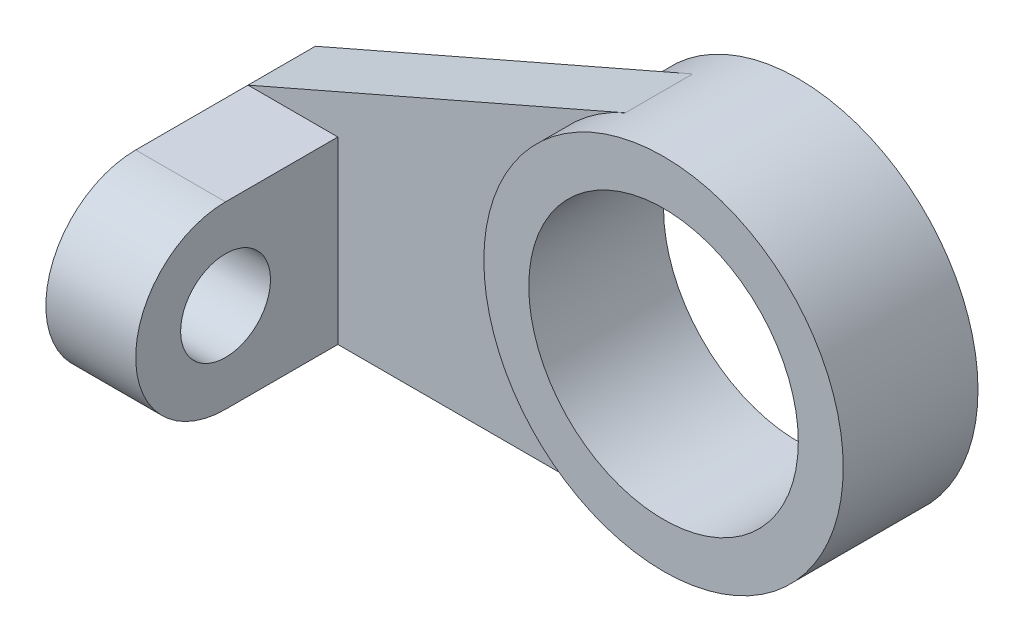
SolidWorks part; units mm, degrees
ref_plane "Front Plane" through (0, 0, 0) normal (0, 0, 1) x (1, 0, 0)
ref_plane "Top Plane" through (0, 0, 0) normal (0, 1, 0) x (1, 0, 0)
ref_plane "Right Plane" through (0, 0, 0) normal (1, 0, 0) x (0, 0, -1)
sketch "Sketch1" plane through (0, 0, 0) normal (0, 0, 1) x (1, 0, 0)
  circle A0 centre (0, 0) radius 38.1
  circle A1 centre (0, 0) radius 50.8
  dimension "D1" = 76.2
  dimension "D2" = 101.6
extrude "Boss-Extrude1" add sketch "Sketch1" along normal mid plane 38.1 contours A0 | A1
sketch "Sketch2" plane through (0, 0, 0) normal (0, 0, 1) x (1, 0, 0)
  line L0 (0, -50.8) -> (-127, -50.8)
  line L1 (-127, -50.8) -> (-127, 0)
  line L2 (-127, 0) -> (-20.32, 46.559)
  circle A0 centre (0, 0) radius 50.8 construction
  arc A1 (-20.32, 46.559) -> (0, -50.8) centre (0, 0) ccw
  dimension "D1" = 127
  dimension "D2" = 50.8
extrude "Boss-Extrude2" add sketch "Sketch2" along normal mid plane 19.05
sketch "Sketch3" plane through (0, 0, 9.525) normal (0, 0, 1) x (1, 0, 0)
  line L1 (-127, -50.8) -> (-101.6, -50.8)
  line L2 (-127, -50.8) -> (-127, 0)
  line L3 (-127, 0) -> (-101.6, 0)
  line L4 (-101.6, -50.8) -> (-101.6, 0)
  dimension "D1" = 25.4
  dimension "D2" = 50.8
extrude "Boss-Extrude3" add sketch "Sketch3" along normal blind 31.75
sketch "Sketch4" plane through (-127, 0, 0) normal (-1, 0, 0) x (0, 0, 1)
  line L0 (41.275, 0) -> (41.275, -50.8) construction
  circle A0 centre (41.275, -25.4) radius 12.7
  circle A1 centre (41.275, -25.4) radius 25.4
  dimension "D1" = 25.4
  dimension "D2" = 50.8
extrude "Boss-Extrude5" add sketch "Sketch4" against normal blind 25.4 contours A0 | A1
sketch "Sketch5" plane through (-127, 0, 0) normal (-1, 0, 0) x (0, 0, 1)
  line L0 (41.275, -12.7) -> (41.275, -38.1) construction
  circle A0 centre (41.275, -25.4) radius 12.7
  dimension "D1" = 25.4
extrude "Cut-Extrude1" cut sketch "Sketch5" against normal through all
